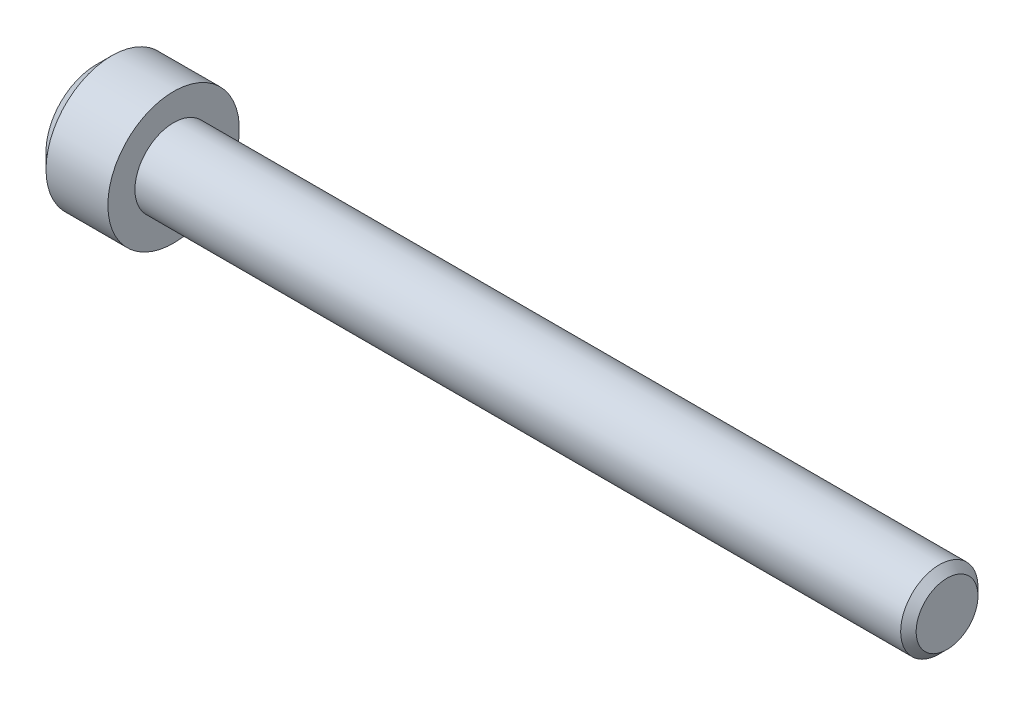
SolidWorks part; units mm, degrees
ref_plane "前视基准面" through (0, 0, 0) normal (0, 0, 1) x (1, 0, 0)
ref_plane "上视基准面" through (0, 0, 0) normal (0, 1, 0) x (1, 0, 0)
ref_plane "右视基准面" through (0, 0, 0) normal (1, 0, 0) x (0, 0, -1)
sketch "草图1" plane through (0, 0, 0) normal (0, 0, 1) x (1, 0, 0)
  line L0 (0, 0) -> (0, 2.5)
  line L1 (0, 2.5) -> (-50, 2.5)
  line L2 (-50, 2.5) -> (-50, 4.25)
  line L3 (-50, 4.25) -> (-55, 4.25)
  line L4 (-55, 4.25) -> (-55, 0)
  line L5 (-55, 0) -> (0, 0)
  line L6 (0, 0) -> (4.7488, 0) construction
  dimension "D1" = 5
  dimension "D2" = 50
  dimension "D3" = 5
  dimension "D4" = 8.5
revolve "旋转1" add sketch "草图1" angle 360 about L6
cosmetic thread "装饰螺纹线1" parameters "D1"=50, "D2"=4.3
chamfer "倒角1" distance 0.5 angle 45 1 edges at (0, 0, 2.5)
sketch "草图2" plane through (-55, 0, 0) normal (-1, 0, 0) x (0, 0, 1)
  line L1 (0, 2.3094) -> (-2, 1.1547)
  line L2 (-2, 1.1547) -> (-2, -1.1547)
  line L3 (-2, -1.1547) -> (0, -2.3094)
  line L4 (0, -2.3094) -> (2, -1.1547)
  line L5 (2, -1.1547) -> (2, 1.1547)
  line L6 (2, 1.1547) -> (0, 2.3094)
  circle A0 centre (0, 0) radius 2 construction
  dimension "D1" = 4
extrude "切除-拉伸1" cut sketch "草图2" against normal blind 2.5
chamfer "倒角2" distance 1 angle 45 1 edges at (-55, 0, 4.25)
sketch "草图4" plane through (-52.5, 0, 0) normal (-1, 0, 0) x (0, 0, 1)
  line L1 (0, -2.3094) -> (2, -1.1547)
  line L2 (2, -1.1547) -> (2, 1.1547)
  line L3 (2, 1.1547) -> (0, 2.3094)
  line L4 (0, 2.3094) -> (-2, 1.1547)
  line L5 (-2, 1.1547) -> (-2, -1.1547)
  line L6 (2, 1.1547) -> (0, 2.3094)
  line L7 (0, 2.3094) -> (-2, 1.1547)
  line L8 (-2, 1.1547) -> (-2, -1.1547)
  line L9 (-2, -1.1547) -> (0, -2.3094)
  line L10 (0, -2.3094) -> (2, -1.1547)
  line L11 (2, -1.1547) -> (2, 1.1547)
  line L12 (2, 1.1547) -> (0, 2.3094) construction
  line L13 (0, 2.3094) -> (-2, 1.1547) construction
  line L14 (-2, 1.1547) -> (-2, -1.1547) construction
  line L15 (-2, -1.1547) -> (0, -2.3094) construction
  line L16 (0, -2.3094) -> (2, -1.1547) construction
  line L17 (2, -1.1547) -> (2, 1.1547) construction
  line L18 (-2, -1.1547) -> (0, -2.3094)
  circle A0 centre (0, 0) radius 2 construction
  dimension "D1" = 0
extrude "切除-拉伸2" cut sketch "草图4" against normal through all draft 59
